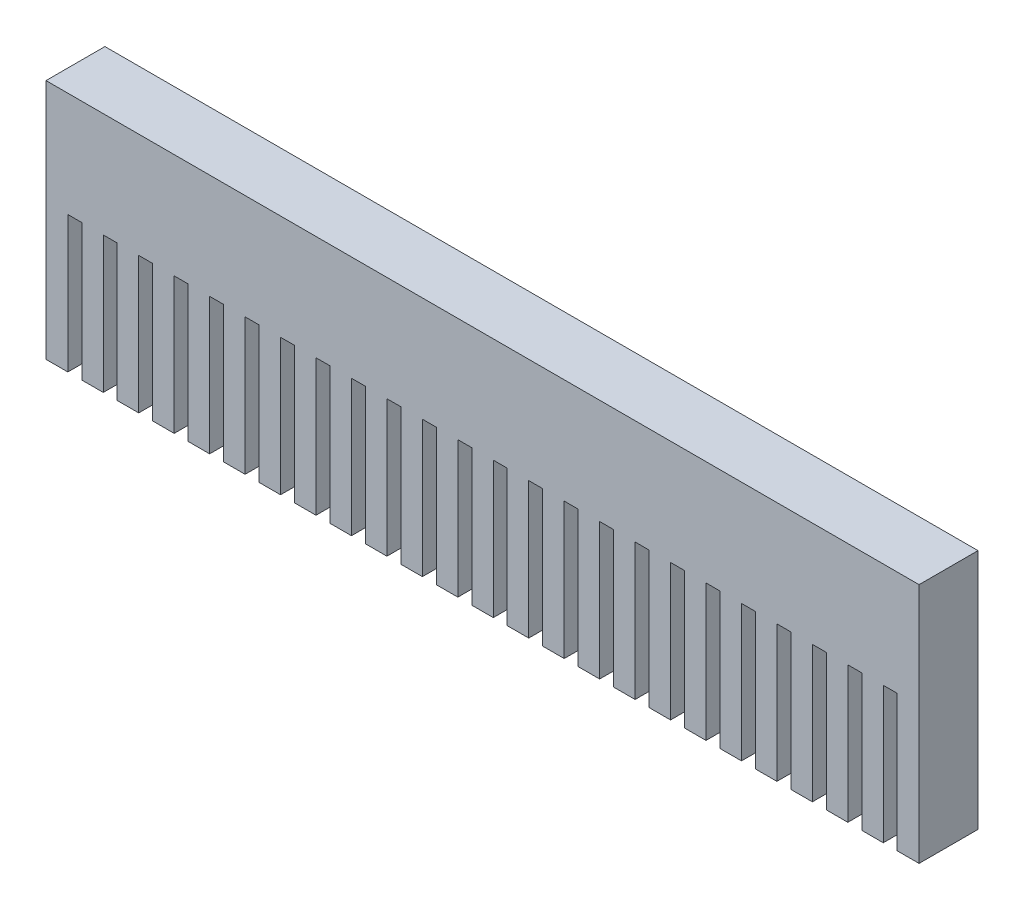
SolidWorks part; units mm, degrees
ref_plane "Front Plane" through (0, 0, 0) normal (0, 0, 1) x (1, 0, 0)
ref_plane "Top Plane" through (0, 0, 0) normal (0, 1, 0) x (1, 0, 0)
ref_plane "Right Plane" through (0, 0, 0) normal (1, 0, 0) x (0, 0, -1)
sketch "Sketch1" plane through (0, 0, 0) normal (0, 0, 1) x (1, 0, 0)
  line L0 (33.32, 0) -> (53.327, 0)
  line L1 (0, 0) -> (20.32, 0)
  line L2 (0, 0) -> (0, 224.79)
  line L3 (0, 224.79) -> (812.8, 224.79)
  line L4 (812.8, 0) -> (812.8, 224.79)
  line L6 (20.32, 0) -> (20.32, 127)
  line L7 (20.32, 127) -> (33.32, 127)
  line L8 (33.32, 0) -> (33.32, 127)
  line L9 (66.327, 0) -> (66.327, 127)
  line L10 (53.327, 0) -> (53.327, 127)
  line L11 (53.327, 127) -> (66.327, 127)
  line L12 (99.3339, 0) -> (99.3339, 127)
  line L13 (86.3339, 0) -> (86.3339, 127)
  line L14 (86.3339, 127) -> (99.3339, 127)
  line L15 (132.3409, 0) -> (132.3409, 127)
  line L16 (119.3409, 0) -> (119.3409, 127)
  line L17 (119.3409, 127) -> (132.3409, 127)
  line L18 (165.3478, 0) -> (165.3478, 127)
  line L19 (152.3478, 0) -> (152.3478, 127)
  line L20 (152.3478, 127) -> (165.3478, 127)
  line L21 (198.3548, 0) -> (198.3548, 127)
  line L22 (185.3548, 0) -> (185.3548, 127)
  line L23 (185.3548, 127) -> (198.3548, 127)
  line L24 (231.3617, 0) -> (231.3617, 127)
  line L25 (218.3617, 0) -> (218.3617, 127)
  line L26 (218.3617, 127) -> (231.3617, 127)
  line L27 (264.3687, 0) -> (264.3687, 127)
  line L28 (251.3687, 0) -> (251.3687, 127)
  line L29 (251.3687, 127) -> (264.3687, 127)
  line L30 (297.3757, 0) -> (297.3757, 127)
  line L31 (284.3757, 0) -> (284.3757, 127)
  line L32 (284.3757, 127) -> (297.3757, 127)
  line L33 (330.3826, 0) -> (330.3826, 127)
  line L34 (317.3826, 0) -> (317.3826, 127)
  line L35 (317.3826, 127) -> (330.3826, 127)
  line L36 (363.3896, 0) -> (363.3896, 127)
  line L37 (350.3896, 0) -> (350.3896, 127)
  line L38 (350.3896, 127) -> (363.3896, 127)
  line L39 (396.3965, 0) -> (396.3965, 127)
  line L40 (383.3965, 0) -> (383.3965, 127)
  line L41 (383.3965, 127) -> (396.3965, 127)
  line L42 (429.4035, 0) -> (429.4035, 127)
  line L43 (416.4035, 0) -> (416.4035, 127)
  line L44 (416.4035, 127) -> (429.4035, 127)
  line L45 (462.4104, 0) -> (462.4104, 127)
  line L46 (449.4104, 0) -> (449.4104, 127)
  line L47 (449.4104, 127) -> (462.4104, 127)
  line L48 (495.4174, 0) -> (495.4174, 127)
  line L49 (482.4174, 0) -> (482.4174, 127)
  line L50 (482.4174, 127) -> (495.4174, 127)
  line L51 (528.4243, 0) -> (528.4243, 127)
  line L52 (515.4243, 0) -> (515.4243, 127)
  line L53 (515.4243, 127) -> (528.4243, 127)
  line L54 (561.4313, 0) -> (561.4313, 127)
  line L55 (548.4313, 0) -> (548.4313, 127)
  line L56 (548.4313, 127) -> (561.4313, 127)
  line L57 (594.4383, 0) -> (594.4383, 127)
  line L58 (581.4383, 0) -> (581.4383, 127)
  line L59 (581.4383, 127) -> (594.4383, 127)
  line L60 (627.4452, 0) -> (627.4452, 127)
  line L61 (614.4452, 0) -> (614.4452, 127)
  line L62 (614.4452, 127) -> (627.4452, 127)
  line L63 (660.4522, 0) -> (660.4522, 127)
  line L64 (647.4522, 0) -> (647.4522, 127)
  line L65 (647.4522, 127) -> (660.4522, 127)
  line L66 (693.4591, 0) -> (693.4591, 127)
  line L67 (680.4591, 0) -> (680.4591, 127)
  line L68 (680.4591, 127) -> (693.4591, 127)
  line L69 (726.4661, 0) -> (726.4661, 127)
  line L70 (713.4661, 0) -> (713.4661, 127)
  line L71 (713.4661, 127) -> (726.4661, 127)
  line L72 (759.473, 0) -> (759.473, 127)
  line L73 (746.473, 0) -> (746.473, 127)
  line L74 (746.473, 127) -> (759.473, 127)
  line L75 (792.48, 0) -> (792.48, 127)
  line L76 (779.48, 0) -> (779.48, 127)
  line L77 (779.48, 127) -> (792.48, 127)
  line L78 (792.48, 0) -> (812.8, 0)
  line L79 (759.473, 0) -> (779.48, 0)
  line L80 (726.4661, 0) -> (746.473, 0)
  line L81 (693.4591, 0) -> (713.4661, 0)
  line L82 (660.4522, 0) -> (680.4591, 0)
  line L83 (627.4452, 0) -> (647.4522, 0)
  line L84 (594.4383, 0) -> (614.4452, 0)
  line L85 (561.4313, 0) -> (581.4383, 0)
  line L86 (528.4243, 0) -> (548.4313, 0)
  line L87 (495.4174, 0) -> (515.4243, 0)
  line L88 (462.4104, 0) -> (482.4174, 0)
  line L89 (429.4035, 0) -> (449.4104, 0)
  line L90 (396.3965, 0) -> (416.4035, 0)
  line L91 (363.3896, 0) -> (383.3965, 0)
  line L92 (330.3826, 0) -> (350.3896, 0)
  line L93 (297.3757, 0) -> (317.3826, 0)
  line L94 (264.3687, 0) -> (284.3757, 0)
  line L95 (231.3617, 0) -> (251.3687, 0)
  line L96 (198.3548, 0) -> (218.3617, 0)
  line L97 (165.3478, 0) -> (185.3548, 0)
  line L98 (132.3409, 0) -> (152.3478, 0)
  line L99 (99.3339, 0) -> (119.3409, 0)
  line L100 (66.327, 0) -> (86.3339, 0)
  dimension "D1" = 812.8
  dimension "D2" = 224.79
  dimension "D3" = 127
  dimension "D4" = 13
  dimension "D5" = 20.32
  dimension "D7" = 20.32
  dimension "D6" = 24
extrude "Boss-Extrude1" add sketch "Sketch1" along normal blind 54.864
